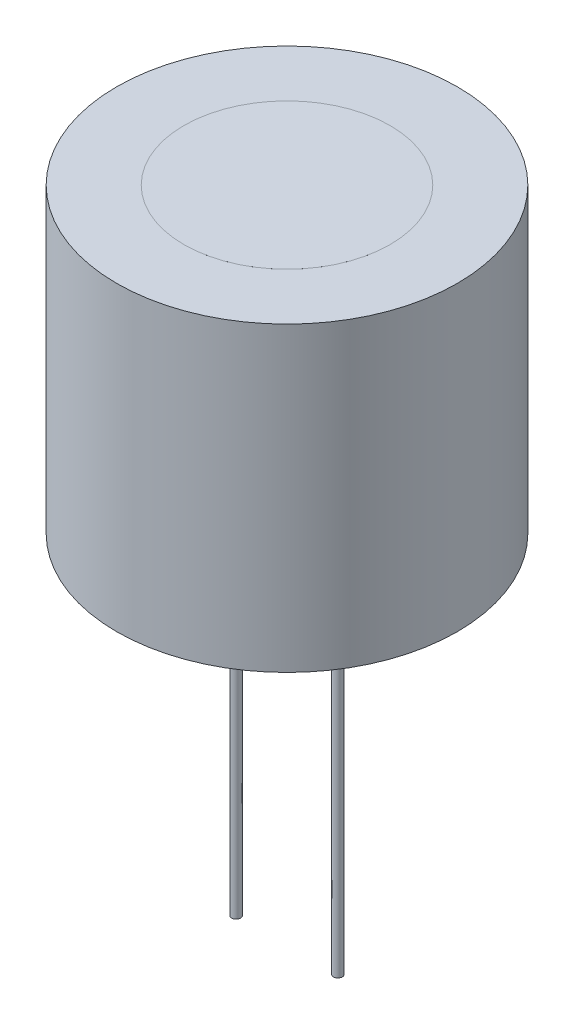
SolidWorks part; units mm, degrees
ref_plane "Front Plane" through (0, 0, 0) normal (0, 0, 1) x (1, 0, 0)
ref_plane "Top Plane" through (0, 0, 0) normal (0, 1, 0) x (1, 0, 0)
ref_plane "Right Plane" through (0, 0, 0) normal (1, 0, 0) x (0, 0, -1)
sketch "Sketch1" plane through (0, 0, 0) normal (0, 1, 0) x (1, 0, 0)
  circle A0 centre (0, 0) radius 8.4963
extrude "Boss-Extrude1" add sketch "Sketch1" against normal blind 15.0495
sketch "Sketch2" plane through (0, 0, 0) normal (0, 1, 0) x (1, 0, 0)
  circle A0 centre (0, 0) radius 5.1435
ref_plane "Plane1" through (0, -15.0495, 0) normal (0, -1, 0) x (-1, 0, 0)
sketch "Sketch3" plane through (0, -15.0495, 0) normal (0, -1, 0) x (-1, 0, 0)
  circle A0 centre (2.54, 0) radius 0.2223
  circle A1 centre (-2.54, 0) radius 0.2223
extrude "Boss-Extrude2" add sketch "Sketch3" along normal blind 17.78
extrude "Boss-Extrude3" add sketch "Sketch2" along normal blind 0.0003 contours A0
